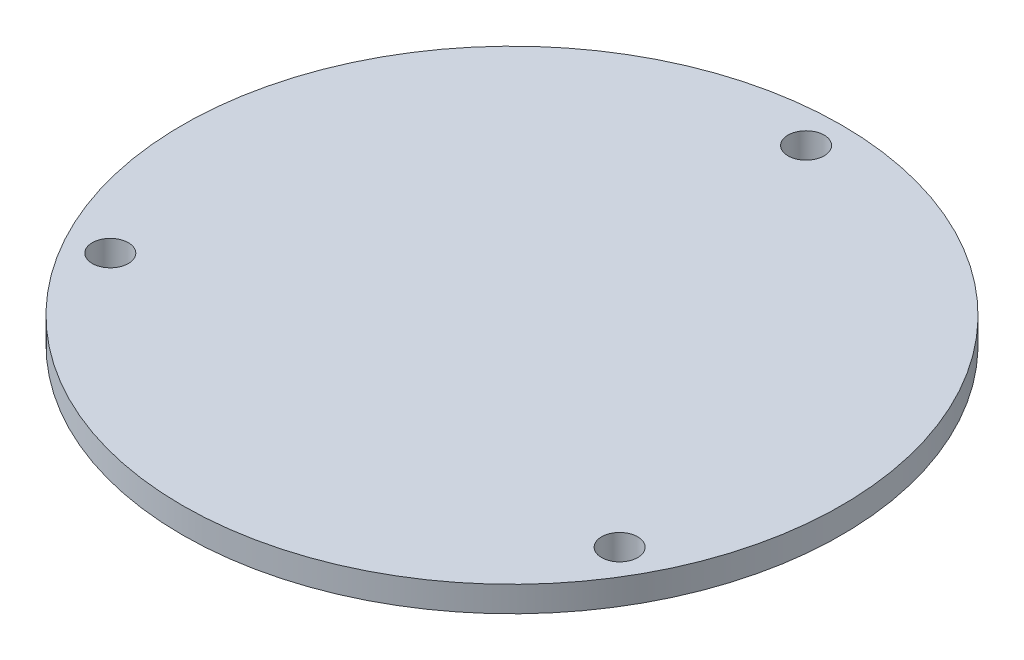
SolidWorks part; units mm, degrees
material "PCB 1"
ref_plane "Front Plane" through (0, 0, 0) normal (0, 0, 1) x (1, 0, 0)
ref_plane "Top Plane" through (0, 0, 0) normal (0, 1, 0) x (1, 0, 0)
ref_plane "Right Plane" through (0, 0, 0) normal (1, 0, 0) x (0, 0, -1)
sketch "Sketch1" plane through (0, 0, 0) normal (0, 1, 0) x (1, 0, 0)
  circle A0 centre (0, 0) radius 20.6375
  dimension "D1" = 41.275
extrude "Boss-Extrude1" add sketch "Sketch1" along normal blind 1.6002
sketch "Sketch2" plane through (0, 0, 0) normal (0, 1, 0) x (1, 0, 0)
  circle A0 centre (0, 18.415) radius 1.1303
  circle A1 centre (15.9479, -9.2075) radius 1.1303
  circle A2 centre (-15.9479, -9.2075) radius 1.1303
  point P10 (0, 0)
  dimension "D1" = 2.2606
  dimension "D2" = 18.415
  dimension "D3" = 3
extrude "Cut-Extrude1" cut sketch "Sketch2" along normal through all and the other way through all contours A0 | A2 | A1
sketch "Sketch4" plane through (0, 0, 0) normal (0, 1, 0) x (1, 0, 0)
  line L1 (-2.54, -2.54) -> (2.54, -2.54)
  line L2 (-2.54, -2.54) -> (-2.54, 2.54)
  line L3 (-2.54, 2.54) -> (2.54, 2.54)
  line L4 (2.54, -2.54) -> (2.54, 2.54)
  line L5 (-2.54, -2.54) -> (2.54, 2.54) construction
  line L6 (-2.54, 2.54) -> (2.54, -2.54) construction
  point P0 (0, 0)
  dimension "D1" = 5.08
  dimension "D2" = 5.08
extrude "Boss-Extrude2" [suppressed] add sketch "Sketch4" along normal blind 6.6799
